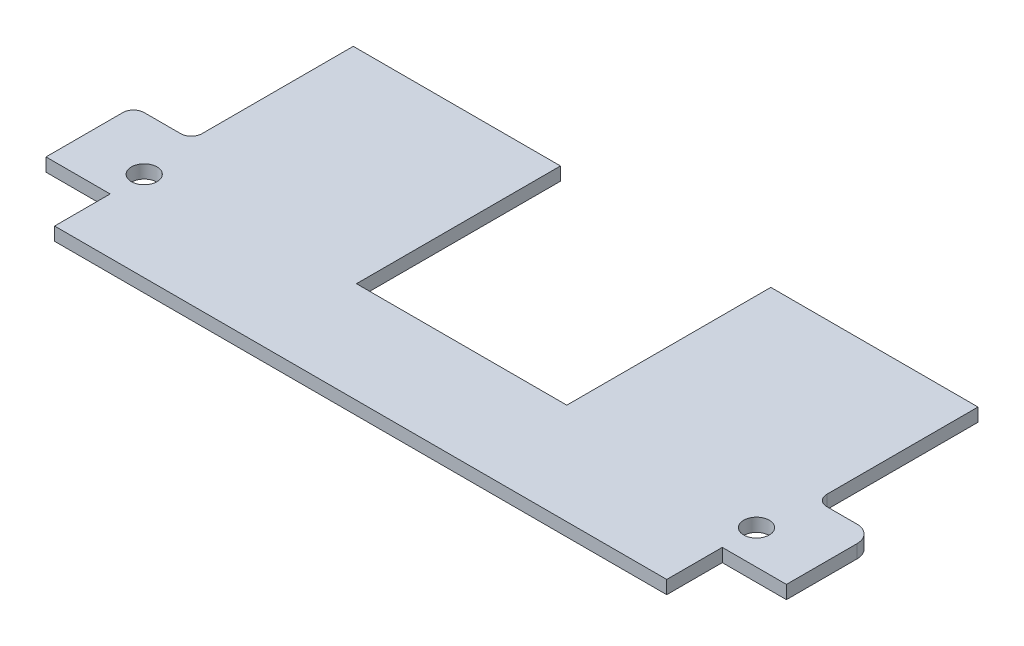
SolidWorks part; units mm, degrees
material "Copper"
ref_plane "Front Plane" through (0, 0, 0) normal (0, 0, 1) x (1, 0, 0)
ref_plane "Top Plane" through (0, 0, 0) normal (0, 1, 0) x (1, 0, 0)
ref_plane "Right Plane" through (0, 0, 0) normal (1, 0, 0) x (0, 0, -1)
sketch "Sketch1" plane through (0, 0, 0) normal (0, 1, 0) x (1, 0, 0)
  line L0 (44.3513, -40.0144) -> (36.7273, -40.0144)
  line L1 (0, 0) -> (0, -46.6159) construction
  line L2 (-12.1487, -17.8713) -> (-12.1487, -10.3704)
  line L3 (-36.0247, -40.0144) -> (-36.0247, -46.6159)
  line L4 (36.7273, -40.0144) -> (36.7273, -46.6159)
  line L5 (-36.0247, -40.0144) -> (-43.6487, -40.0144)
  line L8 (12.8513, -10.3704) -> (12.8513, -17.8713)
  line L11 (30.3773, -46.6159) -> (36.7273, -46.6159)
  line L12 (44.3513, -40.0144) -> (44.3513, -31.6159)
  line L13 (42.3513, -29.6159) -> (38.7463, -29.6159)
  line L14 (37.4763, -28.3459) -> (37.4763, -10.3704)
  line L20 (-36.7737, -10.3704) -> (-36.7737, -28.3459)
  line L21 (-38.0437, -29.6159) -> (-42.3787, -29.6159)
  line L22 (-43.6487, -30.8859) -> (-43.6487, -40.0144)
  line L23 (-36.0247, -46.6159) -> (-29.6747, -46.6159)
  line L24 (-29.6747, -46.6159) -> (30.3773, -46.6159)
  line L25 (-12.1487, -34.6159) -> (12.8513, -34.6159)
  line L26 (-12.1487, -17.8713) -> (-12.1487, -34.6159)
  line L27 (12.8513, -17.8713) -> (12.8513, -34.6159)
  line L28 (-36.7737, -10.3704) -> (-12.1487, -10.3704)
  line L29 (12.8513, -10.3704) -> (37.4763, -10.3704)
  circle A0 centre (-36.0247, -35.9659) radius 1.524
  circle A1 centre (36.7273, -35.9479) radius 1.524
  arc A6 (44.3513, -31.6159) -> (42.3513, -29.6159) centre (42.3513, -31.6159) ccw
  arc A7 (37.4763, -28.3459) -> (38.7463, -29.6159) centre (38.7463, -28.3459) ccw
  arc A13 (-38.0437, -29.6159) -> (-36.7737, -28.3459) centre (-38.0437, -28.3459) ccw
  arc A14 (-42.3787, -29.6159) -> (-43.6487, -30.8859) centre (-42.3787, -30.8859) ccw
  dimension "D1" = 12
  dimension "D3" = 7.624
  dimension "D4" = 7.624
extrude "Boss-Extrude1" add sketch "Sketch1" along normal blind 1.575
